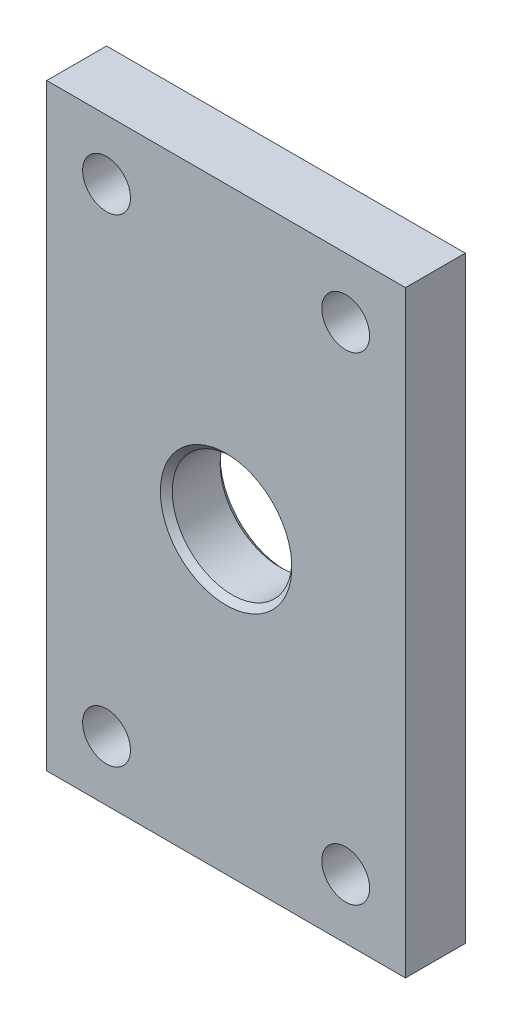
SolidWorks part; units mm, degrees
ref_plane "Front Plane" through (0, 0, 0) normal (1, 0, 0) x (0, 1, 0)
ref_plane "Top Plane" through (0, 0, 0) normal (0, 0, 1) x (0, 1, 0)
ref_plane "Right Plane" through (0, 0, 0) normal (0, 1, 0) x (-1, 0, 0)
sketch "Sketch1" plane through (0, 0, 0) normal (0, 0, 1) x (0, 1, 0)
  line L1 (-50, -30) -> (50, -30)
  line L2 (-50, -30) -> (-50, 30)
  line L3 (-50, 30) -> (50, 30)
  line L4 (50, -30) -> (50, 30)
  line L5 (-50, -30) -> (50, 30) construction
  line L6 (-50, 30) -> (50, -30) construction
  point P0 (0, 0)
  dimension "D1" = 50
  dimension "D2" = 30
extrude "Boss-Extrude1" add sketch "Sketch1" along normal mid plane 10
sketch "Sketch2" plane through (0, 0, 0) normal (0, 0, 1) x (0, 1, 0)
  circle A0 centre (-40, -20) radius 4
  circle A1 centre (40, -20) radius 4
  circle A2 centre (-40, 20) radius 4
  circle A3 centre (40, 20) radius 4
  dimension "D1" = 8
  dimension "D2" = 8
  dimension "D3" = 8
  dimension "D4" = 8
  dimension "D5" = 80
  dimension "D6" = 80
  dimension "D7" = 40
  dimension "D8" = 40
extrude "Cut-Extrude2" cut sketch "Sketch2" against normal through all from offset 5
sketch "Sketch3" plane through (0, 0, 0) normal (0, 0, 1) x (0, 1, 0)
  circle A0 centre (0, 0) radius 10
  dimension "D1" = 20
extrude "Cut-Extrude4" cut sketch "Sketch3" against normal through all from offset 5
chamfer "Chamfer1" distance 1 angle 45 2 edges at (10, 0, -5) (10, 0, 5)
